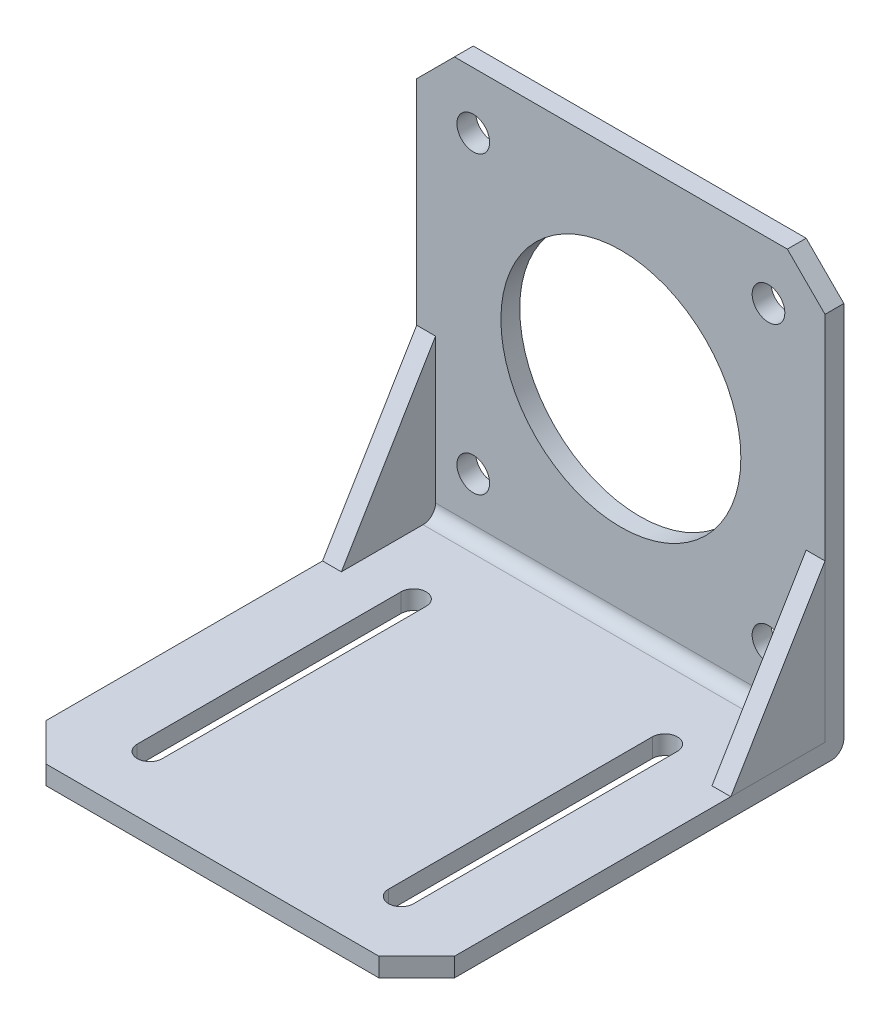
SolidWorks part; units mm, degrees
ref_plane "Front" through (0, 0, 0) normal (0, 0, 1) x (1, 0, 0)
ref_plane "Top" through (0, 0, 0) normal (0, 1, 0) x (1, 0, 0)
ref_plane "Right" through (0, 0, 0) normal (1, 0, 0) x (0, 0, -1)
sketch "Sketch1" plane through (0, 0, 0) normal (0, 0, 1) x (1, 0, 0)
  line L1 (-32.5, -32.5) -> (32.5, -32.5)
  line L2 (-32.5, -32.5) -> (-32.5, 32.5)
  line L3 (-32.5, 32.5) -> (32.5, 32.5)
  line L4 (32.5, -32.5) -> (32.5, 32.5)
  line L5 (-32.5, -32.5) -> (32.5, 32.5) construction
  line L6 (-32.5, 32.5) -> (32.5, -32.5) construction
  point P0 (0, 0)
  dimension "D1" = 65
  dimension "D2" = 65
extrude "Boss-Extrude1" add sketch "Sketch1" along normal blind 3
sketch "Sketch3" plane through (0, -32.5, 0) normal (0, -1, 0) x (-1, 0, 0)
  line L0 (20, -58) -> (20, -16) construction
  line L1 (-32.5, 0) -> (32.5, 0)
  line L2 (-32.5, 0) -> (-32.5, -68)
  line L3 (-32.5, -68) -> (32.5, -68)
  line L4 (32.5, 0) -> (32.5, -68)
  line L5 (18, -58) -> (18, -16)
  line L6 (22, -58) -> (22, -16)
  line L7 (-20, -58) -> (-20, -16) construction
  line L8 (-22, -58) -> (-22, -16)
  line L9 (-18, -58) -> (-18, -16)
  line L10 (20, -37) -> (32.5, -37) construction
  line L11 (-20, -37) -> (-32.5, -37) construction
  arc A0 (18, -58) -> (22, -58) centre (20, -58) ccw
  arc A1 (22, -16) -> (18, -16) centre (20, -16) ccw
  arc A2 (-22, -58) -> (-18, -58) centre (-20, -58) ccw
  arc A3 (-18, -16) -> (-22, -16) centre (-20, -16) ccw
  point P7 (20, -37)
  point P12 (-20, -37)
  dimension "D4" = 2
  dimension "D1" = 68
  dimension "D2" = 65
  dimension "D3" = 42
  dimension "D5" = 40
  dimension "D6" = 10
extrude "Boss-Extrude2" add sketch "Sketch3" along normal blind 3
hole_wizard "Ø5.2 (5.2) Diameter Hole1" positions "Sketch5" profile "Sketch4" hole size "Ø5.2" standard "ANSI Metric"
sketch "Sketch5" plane through (0, 0, 3) normal (0, 0, 1) x (1, 0, 0)
  line L1 (-23.5, 23.5) -> (0, 0) construction
  line L2 (0, 0) -> (23.5, -23.5) construction
  line L3 (0, 0) -> (23.5, 23.5) construction
  line L4 (0, 0) -> (-23.5, -23.5) construction
  point P0 (-23.5, 23.5)
  point P2 (23.5, 23.5)
  point P4 (23.5, -23.5)
  point P6 (-23.5, -23.5)
  dimension "D1" = 47
  dimension "D2" = 47
sketch "Sketch4" plane through (-23.5, 23.5, 3) normal (1, 0, 0) x (0, -1, 0)
  line L0 (0, 0) -> (0, 26.9622)
  line L1 (0, 26.9622) -> (2.6, 25.4)
  line L2 (2.6, 25.4) -> (2.6, 0)
  line L5 (2.6, 0) -> (0, 0)
  line L10 (0, 26.9622) -> (-2.6, 25.4) construction
  line L11 (0, -6.35) -> (0, 107.95) construction
  dimension "Hole Dia." = 5.2
  dimension "Hole Depth" = 25.4
  dimension "Drill Angle" = 118
hole_wizard "Ø5.2 (5.2) Diameter Hole2" positions "Sketch7" profile "Sketch6" hole size "Ø5.2" standard "ANSI Metric"
sketch "Sketch7" plane through (0, 0, 3) normal (0, 0, 1) x (1, 0, 0)
  point P0 (0, 0)
sketch "Sketch6" plane through (0, 0, 3) normal (1, 0, 0) x (0, -1, 0)
  line L0 (0, 0) -> (0, 36.8764)
  line L1 (0, 36.8764) -> (19.1, 25.4)
  line L2 (19.1, 25.4) -> (19.1, 0)
  line L5 (19.1, 0) -> (0, 0)
  line L10 (0, 36.8764) -> (-19.1, 25.4) construction
  line L11 (0, -6.35) -> (0, 107.95) construction
  dimension "Hole Dia." = 38.2
  dimension "Hole Depth" = 25.4
  dimension "Drill Angle" = 118
fillet "Fillet1" radius 2 2 edges at (0, -35.5, 0)
sketch "Sketch8" plane through (32.5, 0, 0) normal (1, 0, 0) x (0, 0, -1)
  line L0 (-3, -7.5) -> (-18, -32.5)
  line L1 (-3, -30.5) -> (-3, 32.5) construction
  line L2 (-5, -32.5) -> (-68, -32.5) construction
  line L3 (-3, -7.5) -> (-3, -32.5)
  line L4 (-3, -32.5) -> (-18, -32.5)
  dimension "D1" = 15
  dimension "D2" = 25
extrude "Boss-Extrude3" add sketch "Sketch8" against normal blind 3 separate body
sketch "Sketch9" plane through (-32.5, 0, 0) normal (-1, 0, 0) x (0, 0, 1)
  line L0 (3, -7.5) -> (18, -32.5)
  line L1 (3, 32.5) -> (3, -30.5) construction
  line L2 (68, -32.5) -> (5, -32.5) construction
  line L3 (18, -32.5) -> (3, -32.5)
  line L4 (3, -32.5) -> (3, -7.5)
  dimension "D1" = 15
  dimension "D2" = 25
extrude "Boss-Extrude4" add sketch "Sketch9" against normal blind 3 separate body
chamfer "Chamfer1" distance 6 angle 45 4 edges at (-32.5, 32.5, 1.5) (-32.5, -34, 68) (32.5, -34, 68) (32.5, 32.5, 1.5)
